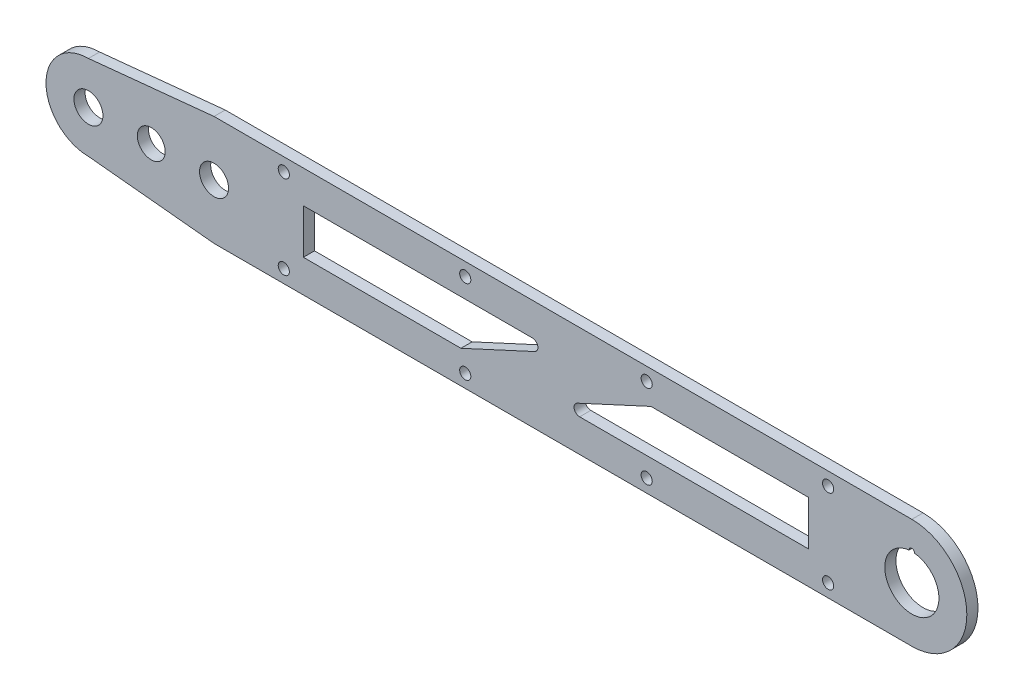
SolidWorks part; units mm, degrees
ref_plane "前视基准面" through (0, 0, 0) normal (0, 0, 1) x (1, 0, 0)
ref_plane "上视基准面" through (0, 0, 0) normal (0, 1, 0) x (1, 0, 0)
ref_plane "右视基准面" through (0, 0, 0) normal (1, 0, 0) x (0, 0, -1)
sketch "草图1" plane through (0, 0, 0) normal (0, 0, 1) x (1, 0, 0)
  line L0 (0, 0) -> (250, 0) construction
  line L1 (0, 0) -> (0, 15.4343) construction
  line L6 (0, 0) -> (0, -15.4343) construction
  line L7 (0, 0) -> (-45, 0) construction
  line L12 (250, 19.7) -> (0, 19.7)
  line L13 (0, 19.7) -> (-45, 15.2)
  line L14 (-45, -15.2) -> (0, -19.7)
  line L15 (0, -19.7) -> (250, -19.7)
  circle A0 centre (0, 0) radius 5.2
  circle A1 centre (250, 0) radius 9.7
  circle A2 centre (-45, 0) radius 5.2
  circle A3 centre (250, 0) radius 19.7 construction
  circle A4 centre (0, 0) radius 19.7 construction
  circle A5 centre (-45, 0) radius 15.2 construction
  arc A6 (-45, -15.2) -> (-45, 15.2) centre (-45, 0) cw
  arc A7 (250, -19.7) -> (250, 19.7) centre (250, 0) ccw
  dimension "D1" = 250
  dimension "D2" = 19.4
  dimension "D3" = 10.4
  dimension "D6" = 10
  dimension "D4" = 45
extrude "凸台-拉伸1" add sketch "草图1" along normal blind 4
sketch "草图2" plane through (0, 0, 4) normal (0, 0, 1) x (1, 0, 0)
  line L0 (0, 0) -> (250, 0) construction
  line L1 (0, 0) -> (0, -8.921) construction
  circle A0 centre (25, 15) radius 2
  circle A1 centre (90, 15) radius 2
  circle A2 centre (155, 15) radius 2
  circle A3 centre (220, 15) radius 2
  circle A4 centre (90, -15) radius 2
  circle A5 centre (155, -15) radius 2
  circle A6 centre (220, -15) radius 2
  circle A7 centre (25, -15) radius 2
  dimension "D1" = 4
  dimension "D2" = 15
  dimension "D3" = 25
  dimension "D4" = 4
  dimension "D5" = 2
extrude "切除-拉伸1" cut sketch "草图2" against normal blind 10
sketch "草图3" plane through (0, 0, 4) normal (0, 0, 1) x (1, 0, 0)
  line L4 (-45, 0) -> (0, 0) construction
  line L8 (32, 8) -> (32, -8)
  line L9 (32, -8) -> (88.4625, -8)
  line L10 (88.4625, -8) -> (114.8614, 4.1841)
  line L11 (114.0233, 8) -> (32, 8)
  line L17 (156.5375, 8) -> (213, 8)
  line L18 (213, 8) -> (213, -8)
  line L19 (213, -8) -> (130.9767, -8)
  line L20 (130.1386, -4.1841) -> (156.5375, 8)
  arc A2 (130.9767, -8) -> (130.1386, -4.1841) centre (130.9767, -6) cw
  arc A3 (114.8614, 4.1841) -> (114.0233, 8) centre (114.0233, 6) ccw
  circle A4 centre (-22.5, 0) radius 5
  dimension "D1" = 2
extrude "切除-拉伸2" cut sketch "草图3" against normal blind 10
sketch "草图4" plane through (0, 0, 4) normal (0, 0, 1) x (1, 0, 0)
  circle A0 centre (250, 9.7) radius 1
  circle A1 centre (250, 0) radius 9.7 construction
extrude "切除-拉伸3" cut sketch "草图4" against normal blind 10
